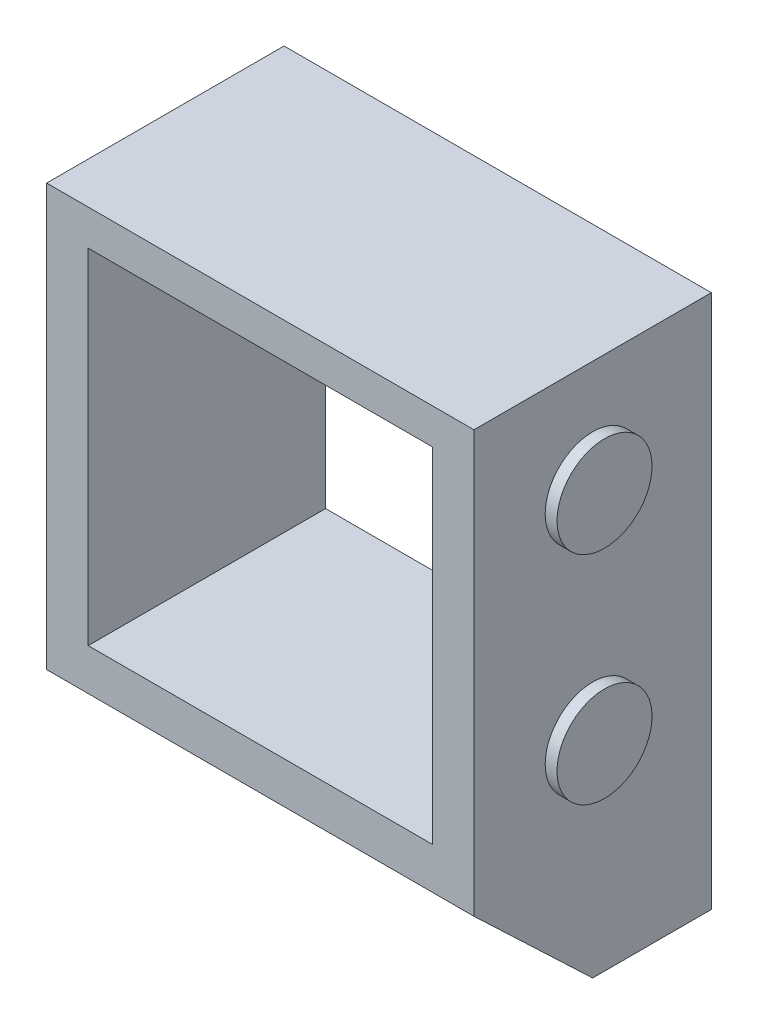
SolidWorks part; units mm, degrees
ref_plane "Front Plane" through (0, 0, 0) normal (0, 0, 1) x (1, 0, 0)
ref_plane "Top Plane" through (0, 0, 0) normal (0, 1, 0) x (1, 0, 0)
ref_plane "Right Plane" through (0, 0, 0) normal (1, 0, 0) x (0, 0, -1)
sketch "Sketch2" plane through (0, 0, 0) normal (0, 0, 1) x (1, 0, 0)
  line L1 (0, 0) -> (914.4, 0)
  line L2 (0, 0) -> (0, 1143)
  line L3 (0, 1143) -> (914.4, 1143)
  line L4 (914.4, 0) -> (914.4, 1143)
  dimension "D1" = 914.4
  dimension "D2" = 1143
extrude "Boss-Extrude1" add sketch "Sketch2" along normal blind 508
sketch "Sketch3" plane through (914.4, 0, 0) normal (1, 0, 0) x (0, 0, -1)
  line L0 (-508, 241.3) -> (-254, 0)
  line L1 (-508, 0) -> (-508, 1143) construction
  line L2 (-508, 0) -> (0, 0) construction
  line L3 (-508, 241.3) -> (-508, 0)
  line L4 (-508, 0) -> (-254, 0)
  point P6 (-508, 242.1353)
extrude "Cut-Extrude1" cut sketch "Sketch3" against normal through all
sketch "Sketch4" plane through (914.4, 0, 0) normal (1, 0, 0) x (0, 0, -1)
  line L0 (-254, 910.6699) -> (-254, 446.9169) construction
  line L1 (0, 678.7934) -> (-508, 678.7934) construction
  line L2 (0, 0) -> (0, 1143) construction
  line L3 (-508, 241.3) -> (-508, 1143) construction
  circle A0 centre (-254, 910.6699) radius 101.6
  circle A1 centre (-254, 446.9169) radius 101.6
  point P4 (-254, 678.7934)
  point P5 (-254, 915.187)
  point P6 (-254, 505.6389)
  point P13 (-254, 446.9169)
extrude "Boss-Extrude2" add sketch "Sketch4" along normal blind 25.4 and the other way blind 939.8
sketch "Sketch5" plane through (0, 0, 508) normal (0, 0, 1) x (1, 0, 0)
  line L0 (0, 1143) -> (914.4, 1143) construction
  line L1 (88.9, 1066.8) -> (825.5, 1066.8)
  line L2 (88.9, 1066.8) -> (88.9, 330.2)
  line L3 (88.9, 330.2) -> (825.5, 330.2)
  line L4 (825.5, 1066.8) -> (825.5, 330.2)
  line L5 (0, 241.3) -> (0, 1143) construction
  line L6 (914.4, 241.3) -> (914.4, 1143) construction
  line L7 (0, 241.3) -> (914.4, 241.3) construction
  dimension "D1" = 76.2
  dimension "D2" = 88.9
  dimension "D3" = 88.9
  dimension "D4" = 88.9
extrude "Cut-Extrude2" cut sketch "Sketch5" against normal up to next
